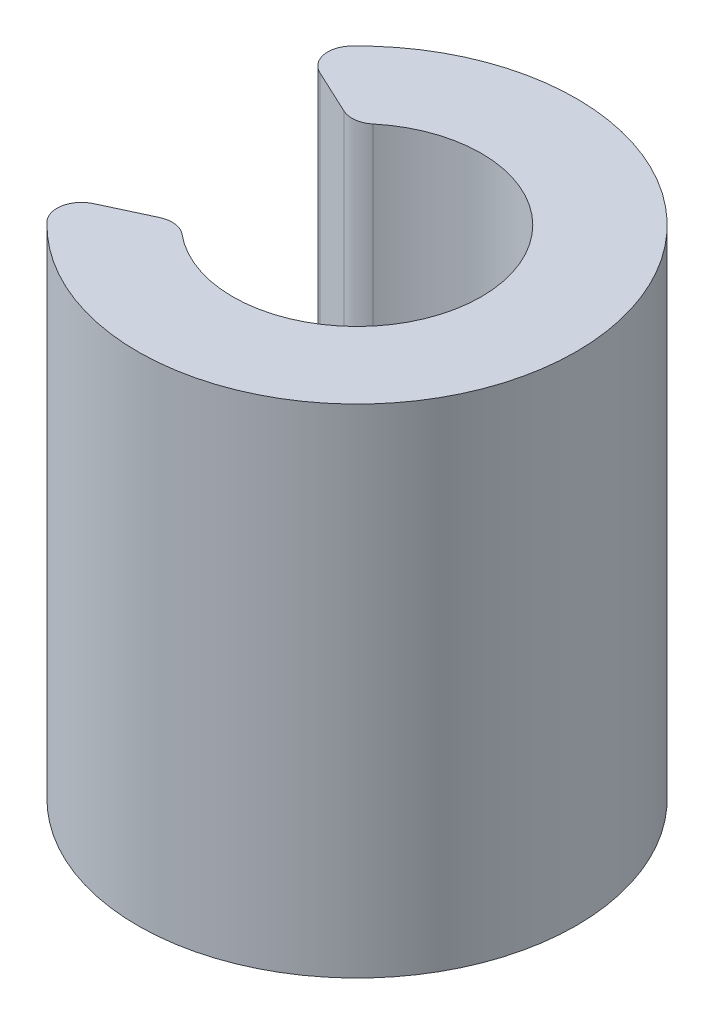
SolidWorks part; units mm, degrees
ref_plane "Alzado" through (0, 0, 0) normal (0, 0, 1) x (1, 0, 0)
ref_plane "Planta" through (0, 0, 0) normal (0, 1, 0) x (1, 0, 0)
ref_plane "Vista lateral" through (0, 0, 0) normal (1, 0, 0) x (0, 0, -1)
sketch "Sketch1" plane through (0, 0, 0) normal (0, 1, 0) x (1, 0, 0)
  line L0 (-3.7094, -3.5) -> (-7.3481, -5.1967)
  line L1 (-7.3481, 5.1967) -> (-3.7094, 3.5)
  line L2 (0, 0) -> (-9, 0) construction
  arc A0 (-7.3481, -5.1967) -> (-7.3481, 5.1967) centre (0, 0) ccw
  arc A1 (-3.7094, -3.5) -> (-3.7094, 3.5) centre (0, 0) ccw
  dimension "D1" = 18
  dimension "D2" = 10.2
  dimension "D3" = 50
  dimension "D4" = 7
extrude "Boss-Extrude1" add sketch "Sketch1" along normal blind 20.4
fillet "Fillet1" radius 1 4 edges at (-7.3481, 10.2, -5.1967) (-7.3481, 10.2, 5.1967) (-3.7094, 10.2, 3.5) (-3.7094, 10.2, -3.5)
